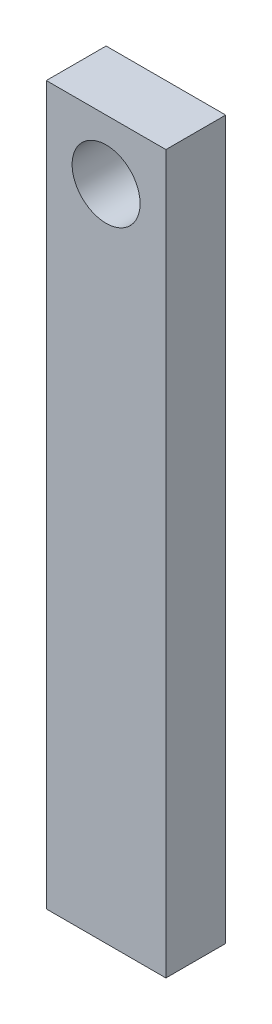
SolidWorks part; units mm, degrees
ref_plane "Front" through (0, 0, 0) normal (0, 0, 1) x (1, 0, 0)
ref_plane "Top" through (0, 0, 0) normal (0, 1, 0) x (1, 0, 0)
ref_plane "Right" through (0, 0, 0) normal (1, 0, 0) x (0, 0, -1)
sketch "草图1" plane through (0, 0, 0) normal (0, 0, 1) x (1, 0, 0)
  line L0 (0, 0) -> (15.9382, 0) construction
  line L1 (-34.1986, 10.3011) -> (-34.1986, 18.4651) construction
  line L2 (-59.5986, 0) -> (-8.7986, 0)
  line L3 (-59.5986, 0) -> (-59.5986, 304.8)
  line L4 (-8.7986, 0) -> (-8.7986, 304.8)
  line L7 (-59.5986, 304.8) -> (-34.1986, 304.8)
  line L8 (-34.1986, 304.8) -> (-8.7986, 304.8)
  circle A1 centre (-34.1986, 279.4) radius 14.4383
  dimension "D1" = 50.8
  dimension "D3" = 25.4
extrude "凸台-拉伸1" add sketch "草图1" along normal blind 25.4
